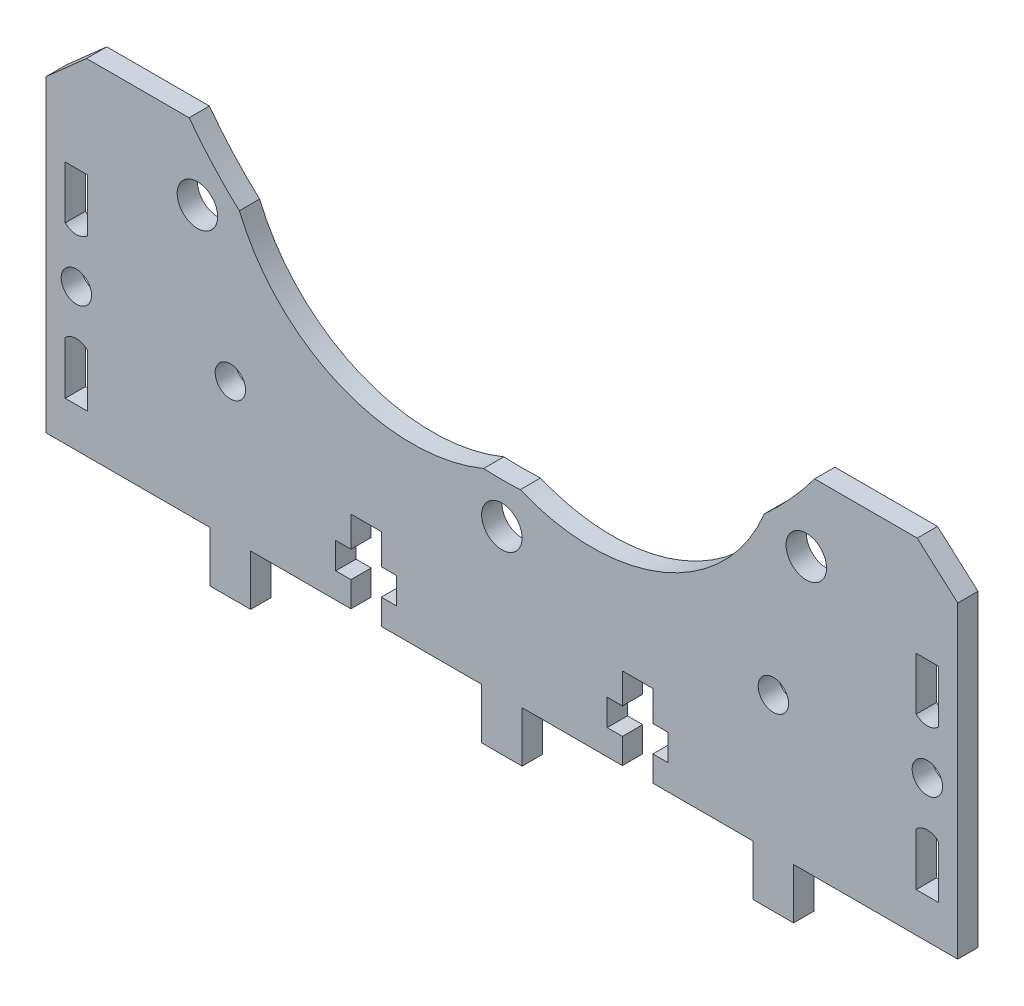
SolidWorks part; units mm, degrees
ref_plane "前视基准面" through (0, 0, 0) normal (0, 0, 1) x (1, 0, 0)
ref_plane "上视基准面" through (0, 0, 0) normal (0, 1, 0) x (1, 0, 0)
ref_plane "右视基准面" through (0, 0, 0) normal (1, 0, 0) x (0, 0, -1)
sketch "草图3" plane through (0, 0, 0) normal (0, 0, 1) x (1, 0, 0)
  line L5 (-45, -3.9902) -> (-28.8, -3.9902)
  line L6 (24.8, -8.9902) -> (24.8, -3.9902)
  line L7 (-28.8, -3.9902) -> (-28.8, -8.9902)
  line L8 (-28.8, -8.9902) -> (-24.8, -8.9902)
  line L9 (-24.8, -8.9902) -> (-24.8, -3.9902)
  line L11 (28.8, -8.9902) -> (24.8, -8.9902)
  line L12 (28.8, -3.9902) -> (28.8, -8.9902)
  line L13 (45, -3.9902) -> (28.8, -3.9902)
  line L39 (-41, 0.0098) -> (-44, 0.0098) construction
  line L40 (-44, 0.0098) -> (-44, 5.0098) construction
  line L41 (-44, 5.0098) -> (-41, 5.0098) construction
  line L55 (-41, 15.0098) -> (-44, 15.0098) construction
  line L56 (-44, 15.0098) -> (-44, 20.0098) construction
  line L57 (-44, 20.0098) -> (-41, 20.0098) construction
  line L82 (0, 10.5098) -> (0, 5.0098) construction
  line L97 (-42, 0.0098) -> (-42, 5.0098) construction
  line L98 (-42, 15.0098) -> (-42, 20.0098) construction
  line L100 (-43.1, 5.1098) -> (-43.1, -0.0902)
  line L101 (-43.1, -0.0902) -> (-40.9, -0.0902)
  line L102 (-40.9, 5.1098) -> (-40.9, -0.0902)
  line L103 (-43.1, 5.1098) -> (-40.9, -0.0902) construction
  line L104 (-43.1, -0.0902) -> (-40.9, 5.1098) construction
  line L106 (-43.1, 20.1098) -> (-40.9, 20.1098)
  line L107 (-43.1, 20.1098) -> (-43.1, 14.9098)
  line L109 (-40.9, 20.1098) -> (-40.9, 14.9098)
  line L110 (-43.1, 20.1098) -> (-40.9, 14.9098) construction
  line L111 (-43.1, 14.9098) -> (-40.9, 20.1098) construction
  line L114 (43.1, 14.9098) -> (40.9, 20.1098) construction
  line L115 (43.1, 20.1098) -> (40.9, 14.9098) construction
  line L116 (43.1, -0.0902) -> (40.9, 5.1098) construction
  line L117 (43.1, 5.1098) -> (40.9, -0.0902) construction
  line L118 (42, 15.0098) -> (42, 20.0098) construction
  line L119 (42, 0.0098) -> (42, 5.0098) construction
  line L120 (44, 20.0098) -> (41, 20.0098) construction
  line L121 (44, 15.0098) -> (44, 20.0098) construction
  line L122 (41, 15.0098) -> (44, 15.0098) construction
  line L123 (44, 5.0098) -> (41, 5.0098) construction
  line L124 (44, 0.0098) -> (44, 5.0098) construction
  line L125 (41, 0.0098) -> (44, 0.0098) construction
  line L126 (40.9, 20.1098) -> (40.9, 14.9098)
  line L128 (43.1, 20.1098) -> (43.1, 14.9098)
  line L129 (43.1, 20.1098) -> (40.9, 20.1098)
  line L130 (40.9, 5.1098) -> (40.9, -0.0902)
  line L131 (43.1, -0.0902) -> (40.9, -0.0902)
  line L132 (43.1, 5.1098) -> (43.1, -0.0902)
  line L137 (41, 30.0098) -> (45, 26.4631)
  line L139 (14.9, -1.4902) -> (16.4, -1.4902)
  line L140 (-30.052, 22.9577) -> (0, 53.0098) construction
  line L141 (-42.5, 53.0098) -> (0, 53.0098) construction
  line L142 (0, 10.5098) -> (0, 53.0098) construction
  line L143 (-44, 5.0098) -> (-44, 15.0098) construction
  line L144 (-45, 15.0098) -> (-45, 5.0098)
  line L145 (-45, -3.9902) -> (-45, 5.0098)
  line L147 (45, 26.4631) -> (45, 15.0098)
  line L148 (45, 5.0098) -> (45, -3.9902)
  line L151 (11.9, 4.1098) -> (14.9, 4.1098)
  line L153 (11.9, -1.4902) -> (10.4, -1.4902)
  line L154 (11.9, -3.9902) -> (11.9, -1.4902)
  line L155 (16.4, -1.4902) -> (16.4, 1.1098)
  line L156 (16.4, 1.1098) -> (14.9, 1.1098)
  line L157 (14.9, 1.1098) -> (14.9, 4.1098)
  line L158 (11.9, 1.1098) -> (11.9, 4.1098)
  line L159 (10.4, 1.1098) -> (11.9, 1.1098)
  line L160 (10.4, -1.4902) -> (10.4, 1.1098)
  line L161 (14.9, -1.4902) -> (14.9, -3.9902)
  line L162 (24.8, -3.9902) -> (14.9, -3.9902)
  line L163 (13.4, -3.9902) -> (13.4, -2.3629) construction
  line L164 (0, -8.9902) -> (-2, -8.9902)
  line L165 (0, -8.9902) -> (2, -8.9902)
  line L166 (2, -8.9902) -> (2, -3.9902)
  line L167 (-2, -8.9902) -> (-2, -3.9902)
  line L168 (-11.9, -1.4902) -> (-10.4, -1.4902)
  line L169 (-14.9, 4.1098) -> (-11.9, 4.1098)
  line L170 (-14.9, -1.4902) -> (-16.4, -1.4902)
  line L171 (-14.9, -3.9902) -> (-14.9, -1.4902)
  line L172 (-10.4, -1.4902) -> (-10.4, 1.1098)
  line L173 (-10.4, 1.1098) -> (-11.9, 1.1098)
  line L174 (-11.9, 1.1098) -> (-11.9, 4.1098)
  line L175 (-14.9, 1.1098) -> (-14.9, 4.1098)
  line L176 (-16.4, 1.1098) -> (-14.9, 1.1098)
  line L177 (-16.4, -1.4902) -> (-16.4, 1.1098)
  line L178 (-11.9, -1.4902) -> (-11.9, -3.9902)
  line L179 (11.9, -3.9902) -> (2, -3.9902)
  line L180 (-13.4, -3.9902) -> (-13.4, -2.3629) construction
  line L182 (-2, -3.9902) -> (-11.9, -3.9902)
  line L183 (-14.9, -3.9902) -> (-24.8, -3.9902)
  line L184 (-41, 30.0098) -> (-45, 26.4631)
  line L186 (-45, 26.4631) -> (-45, 15.0098)
  line L187 (45, 15.0098) -> (45, 5.0098)
  line L188 (-30.8747, 30.0098) -> (-41, 30.0098)
  line L189 (41, 30.0098) -> (30.8747, 30.0098)
  circle A4 centre (0, 10.5098) radius 2
  circle A5 centre (-30.052, 22.9577) radius 2
  circle A11 centre (30.052, 22.9577) radius 2
  circle A13 centre (42.5, 53.0098) radius 2 [skipped]
  circle A14 centre (30.052, 83.0618) radius 2 [skipped]
  circle A15 centre (-30.052, 83.0618) radius 2 [skipped]
  circle A16 centre (0, 95.5098) radius 2 [skipped]
  circle A17 centre (-26.8, 9.5098) radius 1.5
  circle A18 centre (26.8, 9.5098) radius 1.5
  arc A21 (-43.1, 5.1098) -> (-40.9, 5.1098) centre (-42, 4.0098) cw
  arc A22 (-43.1, 14.9098) -> (-40.9, 14.9098) centre (-42, 16.0098) ccw
  arc A23 (40.9, 14.9098) -> (43.1, 14.9098) centre (42, 16.0098) ccw
  arc A24 (40.9, 5.1098) -> (43.1, 5.1098) centre (42, 4.0098) cw
  circle A25 centre (0, 53.0098) radius 42.5 construction
  circle A26 centre (-42, 10.0098) radius 1.5
  circle A29 centre (42, 10.0098) radius 1.5
  circle A30 centre (-42.5, 53.0098) radius 2 [skipped]
  arc A32 (30.8747, 30.0098) -> (-30.8747, 30.0098) centre (0, 53.0098) cw construction
  arc A33 (-1.8098, 14.5523) -> (-25.9127, 24.5356) centre (-8.8696, 31.5954) cw
  arc A34 (1.8098, 14.5523) -> (25.9127, 24.5356) centre (8.8696, 31.5954) ccw
  arc A35 (30.8747, 30.0098) -> (25.9127, 24.5356) centre (0, 53.0098) cw
  arc A36 (1.8098, 14.5523) -> (-1.8098, 14.5523) centre (0, 53.0098) cw
  arc A38 (-25.9127, 24.5356) -> (-30.8747, 30.0098) centre (0, 53.0098) cw
  point P39 (-42, 2.5098)
  point P55 (-42, 17.5098)
  point P90 (42, 17.5098)
  point P91 (42, 2.5098)
  dimension "D1" = 8
extrude "凸台-拉伸1" add sketch "草图3" along normal blind 2
sketch "草图4" plane through (0, -3.9902, 0) normal (0, -1, 0) x (1, 0, 0)
  line L0 (14.9, 0) -> (11.9, 2)
  line L1 (-11.9, 0) -> (-14.9, 2)
  line L2 (-14.9, 2) -> (-14.9, 0) construction
  circle A0 centre (13.4, 1) radius 1.5
  circle A1 centre (-13.4, 1) radius 1.5
